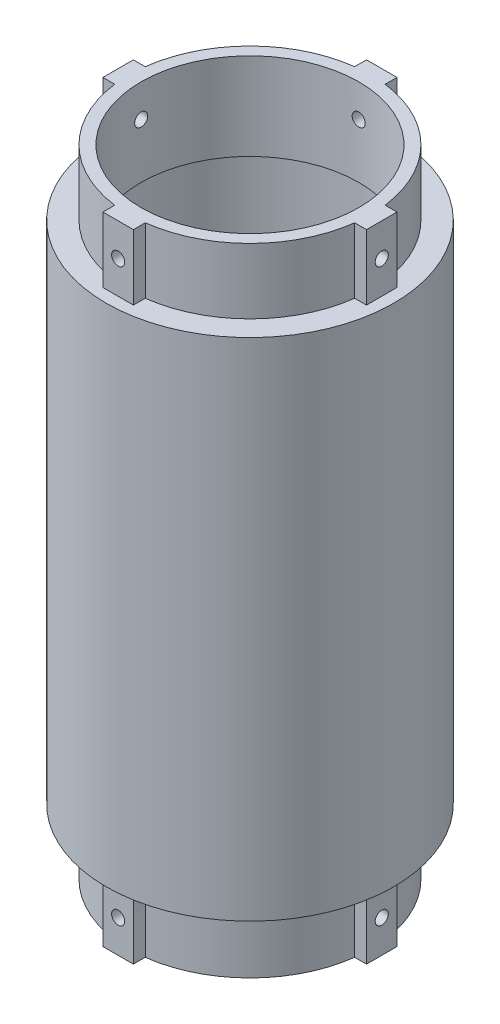
SolidWorks part; units mm, degrees
ref_plane "Alzado" through (0, 0, 0) normal (0, 0, 1) x (1, 0, 0)
ref_plane "Planta" through (0, 0, 0) normal (0, 1, 0) x (1, 0, 0)
ref_plane "Vista lateral" through (0, 0, 0) normal (1, 0, 0) x (0, 0, -1)
sketch "Croquis3" plane through (0, 0, 0) normal (0, 1, 0) x (1, 0, 0)
  circle A0 centre (0, 0) radius 27.75
  circle A1 centre (0, 0) radius 25
  dimension "D1" = 55.5
  dimension "D2" = 50
extrude "Saliente-Extruir1" add sketch "Croquis3" along normal blind 15
sketch "Croquis4" plane through (0, 15, 0) normal (0, 1, 0) x (1, 0, 0)
  circle A0 centre (0, 0) radius 33
  circle A1 centre (0, 0) radius 25
  dimension "D1" = 66
  dimension "D2" = 50
extrude "Saliente-Extruir2" add sketch "Croquis4" along normal blind 5
sketch "Croquis5" plane through (0, 20, 0) normal (0, 1, 0) x (1, 0, 0)
  circle A0 centre (0, 0) radius 33
  circle A1 centre (0, 0) radius 28
  dimension "D1" = 66
  dimension "D2" = 56
extrude "Saliente-Extruir3" add sketch "Croquis5" along normal blind 53
ref_plane "Plano3" through (0, 73, 0) normal (0, 1, 0) x (1, 0, 0)
sketch "Croquis6" plane through (0, 15, 0) normal (0, -1, 0) x (1, 0, 0)
  line L0 (25.25, 3.5) -> (30.25, 3.5)
  line L1 (-3.5, 25.25) -> (3.5, 25.25)
  line L2 (-3.5, 25.25) -> (-3.5, 30.25)
  line L3 (-3.5, 30.25) -> (3.5, 30.25)
  line L4 (3.5, 25.25) -> (3.5, 30.25)
  line L5 (0, 30.25) -> (0, 25.25) construction
  line L6 (-3.5, 27.75) -> (3.5, 27.75) construction
  line L7 (25.25, 3.5) -> (25.25, -3.5)
  line L8 (25.25, -3.5) -> (30.25, -3.5)
  line L9 (30.25, 3.5) -> (30.25, -3.5)
  line L10 (3.5, -25.25) -> (3.5, -30.25)
  line L11 (3.5, -25.25) -> (-3.5, -25.25)
  line L12 (-3.5, -25.25) -> (-3.5, -30.25)
  line L13 (3.5, -30.25) -> (-3.5, -30.25)
  line L14 (-25.25, -3.5) -> (-30.25, -3.5)
  line L15 (-25.25, -3.5) -> (-25.25, 3.5)
  line L16 (-25.25, 3.5) -> (-30.25, 3.5)
  line L17 (-30.25, -3.5) -> (-30.25, 3.5)
  circle A0 centre (0, 0) radius 27.75 construction
  circle A1 centre (0, 0) radius 27.75 construction
  point P0 (0, 27.75)
  point P23 (0, 0)
  dimension "D1" = 2.5
  dimension "D2" = 7
  dimension "D3" = 30.25
  dimension "D4" = 4
extrude "Saliente-Extruir4" add sketch "Croquis6" along normal up to surface (15 mm away) up to face at (0, 0, 27.75)
mirror "Simetría2" about plane through (0, 73, 0) normal (0, 1, 0) of bodies 121
sketch "Croquis7" plane through (-30.25, 0, 0) normal (-1, 0, 0) x (0, 0, 1)
  circle A1 centre (0, 7.5) radius 1.5
extrude "Cortar-Extruir1" cut sketch "Croquis7" against normal through all
sketch "Croquis8" plane through (0, 0, -30.25) normal (0, 0, -1) x (-1, 0, 0)
  circle A1 centre (0, 7.5) radius 1.5
extrude "Cortar-Extruir2" cut sketch "Croquis8" against normal through all
sketch "Croquis9" plane through (-30.25, 0, 0) normal (-1, 0, 0) x (0, 0, 1)
  circle A1 centre (0, 138.5) radius 1.5
extrude "Cortar-Extruir3" cut sketch "Croquis9" against normal through all both and the other way through all
sketch "Croquis10" plane through (0, 0, 30.25) normal (0, 0, 1) x (1, 0, 0)
  circle A1 centre (0, 138.5) radius 1.5
extrude "Cortar-Extruir4" cut sketch "Croquis10" against normal through all both and the other way through all
